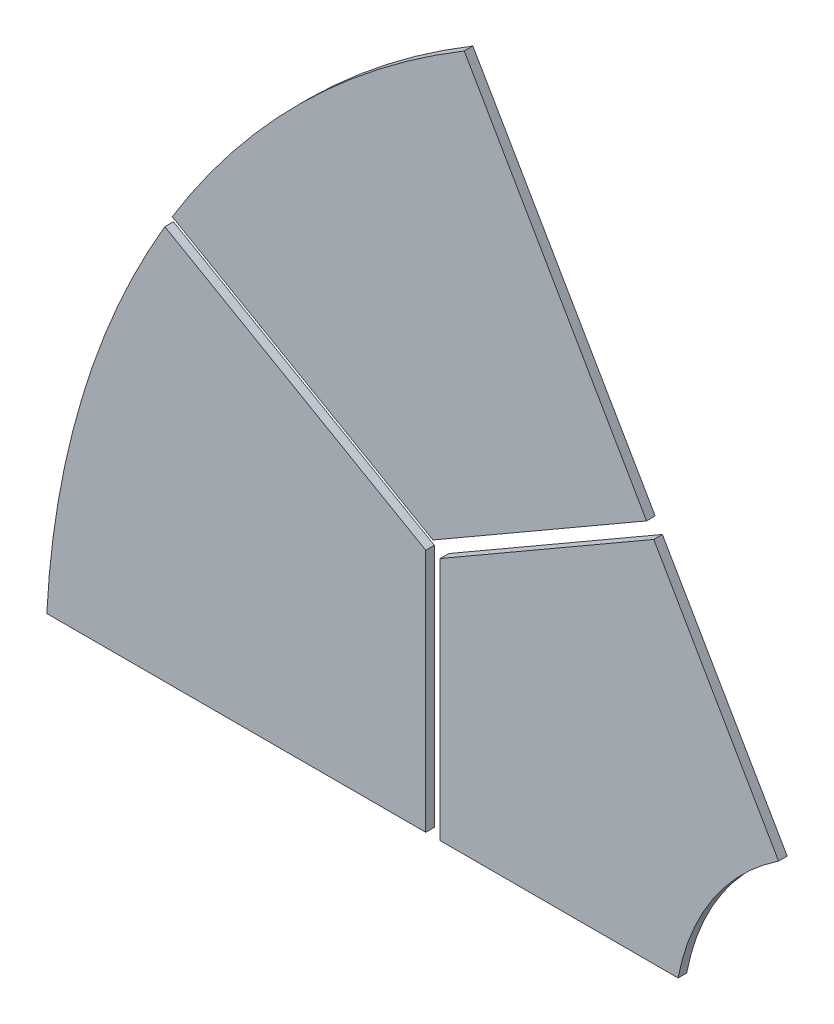
SolidWorks part; units mm, degrees
ref_plane "Front Plane" through (0, 0, 0) normal (0, 0, 1) x (1, 0, 0)
ref_plane "Top Plane" through (0, 0, 0) normal (0, 1, 0) x (1, 0, 0)
ref_plane "Right Plane" through (0, 0, 0) normal (1, 0, 0) x (0, 0, -1)
sketch "Sketch1" plane through (0, 0, 0) normal (0, 0, 1) x (1, 0, 0)
  line L1 (-151.082, 20) -> (-609.6, 20)
  line L2 (-76.2, 131.9823) -> (-304.8, 527.9291)
  line L3 (-520.2684, 317.6995) -> (-520.3687, 317.7571)
  line L4 (-151.082, 20) -> (-609.2718, 20)
  line L5 (-335.2, 199.9666) -> (-516.7369, 304.1433)
  line L6 (-330.2076, 208.6312) -> (-511.5918, 312.7203)
  line L7 (-89.7062, 135.3756) -> (-176.5521, 285.7972)
  line L8 (-159.605, 30) -> (-325.2, 30)
  line L9 (-123.5362, 90.0309) -> (-131.8552, 94.8048)
  line L10 (-325.2, 30) -> (-325.2, 199.9754)
  line L11 (-325.2, 199.9754) -> (-176.5521, 285.7972)
  line L12 (-128.5135, 81.3575) -> (-137.4539, 86.4881)
  line L13 (-335.2, 30) -> (-335.2, 199.9666)
  line L14 (-330.2076, 208.6312) -> (-181.5521, 294.4575)
  line L15 (-181.5521, 294.4575) -> (-308.4186, 514.1966)
  line L16 (-335.2, 30) -> (-598.849, 30)
  line L17 (-89.7062, 135.3756) -> (-308.4186, 514.1966) construction
  line L19 (-159.605, 30) -> (-598.849, 30) construction
  arc A0 (-304.8, 527.9291) -> (-609.2718, 20) centre (0, 0) ccw
  arc A1 (-76.2, 131.9823) -> (-151.082, 20) centre (0, 0) ccw
  arc A2 (-89.7062, 135.3756) -> (-159.605, 30) centre (0, 0) ccw
  arc A3 (-308.4186, 514.1966) -> (-511.5918, 312.7203) centre (0, 0) ccw
  arc A4 (-516.7369, 304.1433) -> (-598.849, 30) centre (0, 0) ccw
  arc A6 (-308.4186, 514.1966) -> (-598.849, 30) centre (0, 0) ccw construction
  point P3 (0, 20)
  point P9 (0, 0)
  dimension "D1" = 10
extrude "Boss-Extrude2" add sketch "Sketch1" along normal blind 6 contours L5 A4 L16 L13 | L15 A3 L6 L14 | A2 L7 L11 L10 L8
